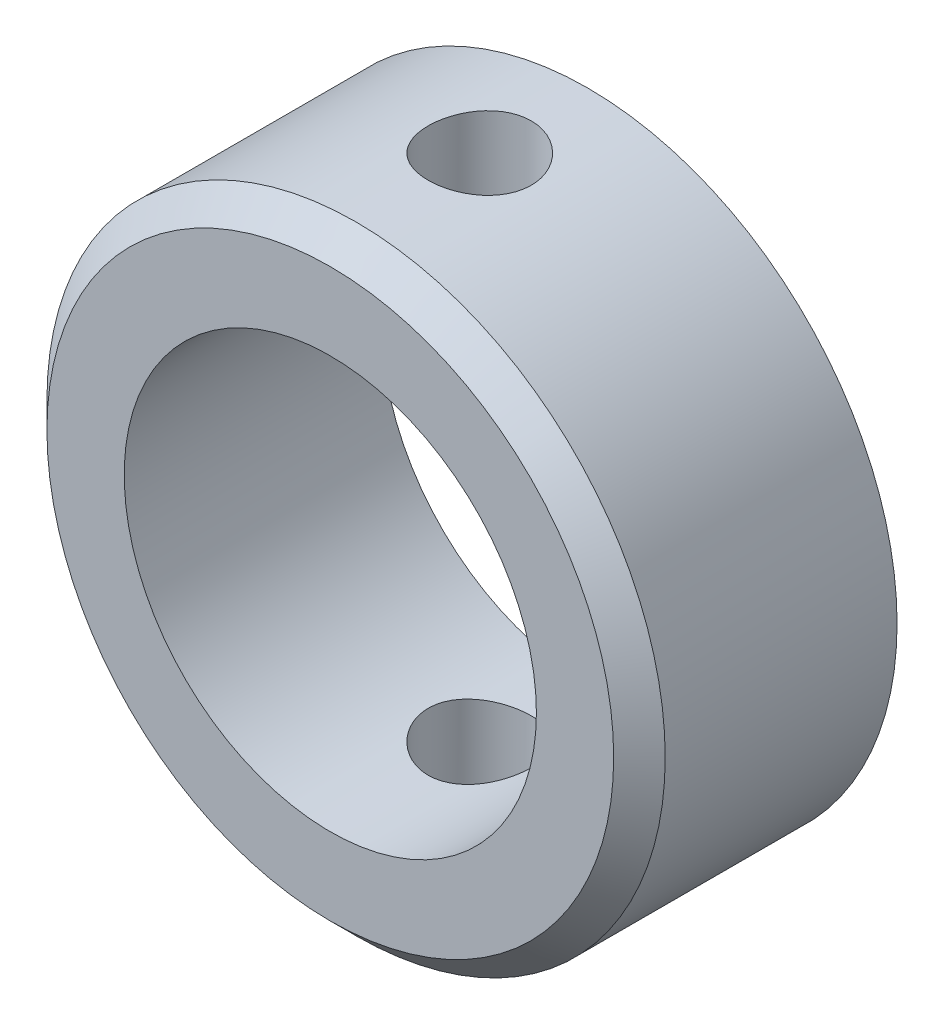
SolidWorks part; units mm, degrees
ref_plane "Front Plane" through (0, 0, 0) normal (0, 0, 1) x (1, 0, 0)
ref_plane "Top Plane" through (0, 0, 0) normal (0, 1, 0) x (1, 0, 0)
ref_plane "Right Plane" through (0, 0, 0) normal (1, 0, 0) x (0, 0, -1)
sketch "Sketch1" plane through (0, 0, 0) normal (0, 0, 1) x (1, 0, 0)
  circle A0 centre (0, 0) radius 8
  circle A1 centre (0, 0) radius 12
  dimension "D1" = 16
  dimension "D2" = 24
extrude "Boss-Extrude1" add sketch "Sketch1" along normal blind 10
chamfer "Chamfer1" distance 1 angle 45 1 edges at (12, 0, 10)
sketch "Sketch2" plane through (0, 0, 0) normal (0, 1, 0) x (1, 0, 0)
  circle A0 centre (0, -4.2) radius 2
  dimension "D1" = 4.2
extrude "Cut-Extrude1" cut sketch "Sketch2" against normal mid plane 54
